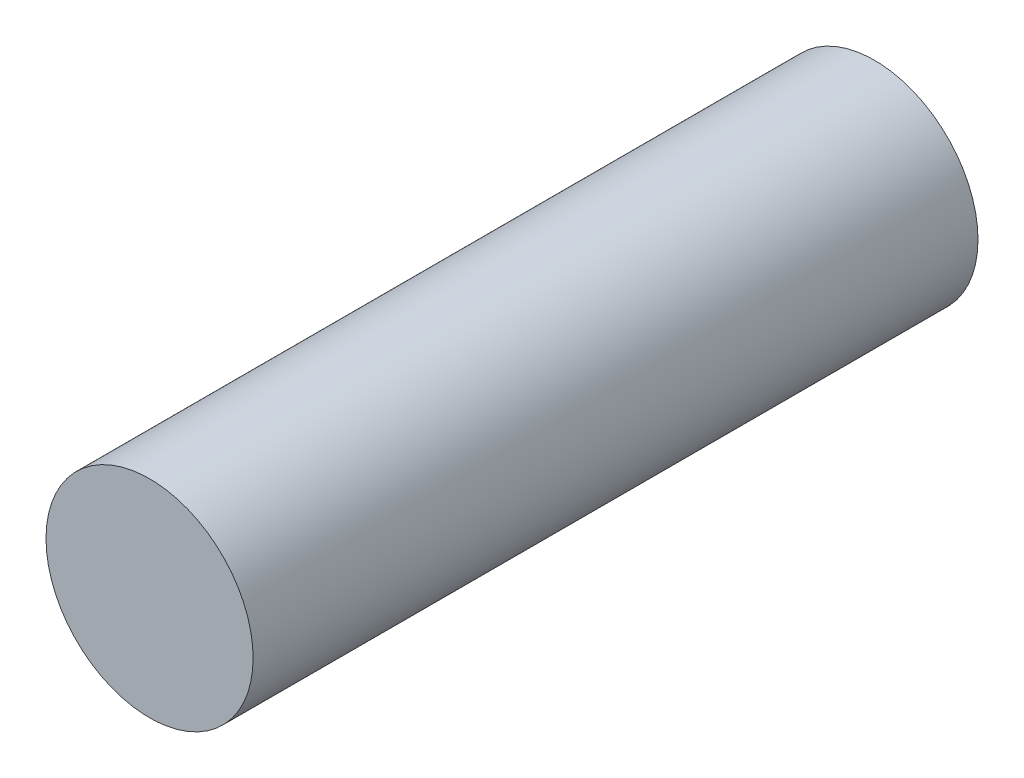
SolidWorks part; units mm, degrees
material "Pine"
ref_plane "Front Plane" through (0, 0, 0) normal (0, 0, 1) x (1, 0, 0)
ref_plane "Top Plane" through (0, 0, 0) normal (0, 1, 0) x (1, 0, 0)
ref_plane "Right Plane" through (0, 0, 0) normal (1, 0, 0) x (0, 0, -1)
sketch "Sketch1" plane through (0, 0, 0) normal (0, 0, 1) x (1, 0, 0)
  circle A0 centre (-2.0451, 0) radius 2
  dimension "D1" = 4
extrude "Boss-Extrude1" add sketch "Sketch1" along normal blind 14
